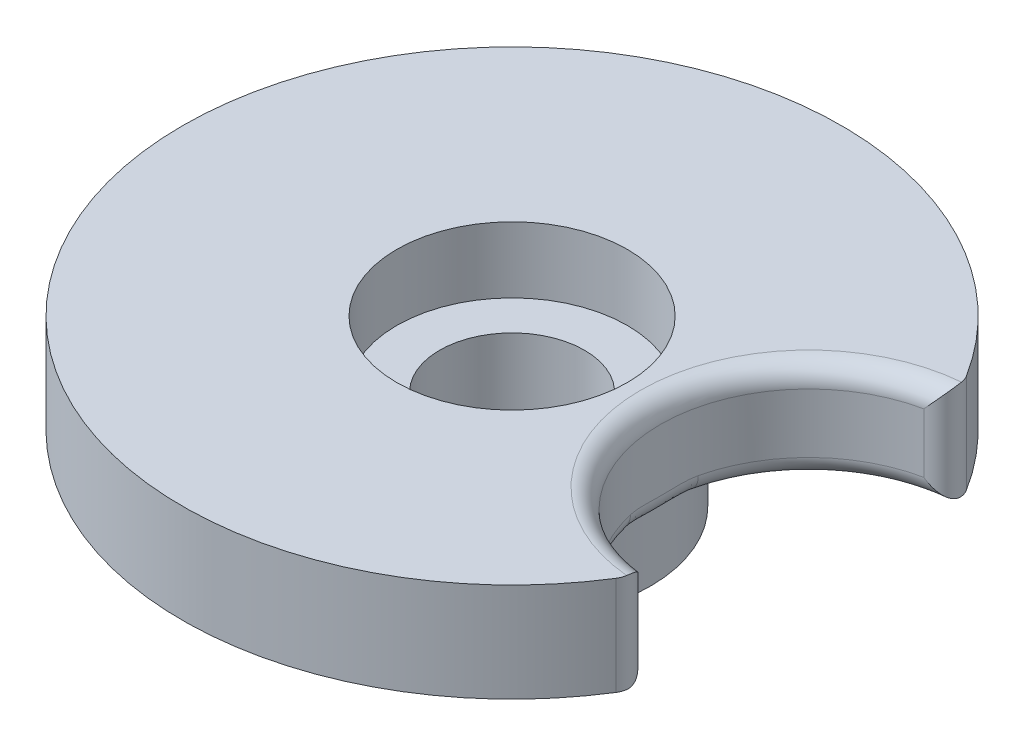
SolidWorks part; units mm, degrees
ref_plane "Front Plane" through (0, 0, 0) normal (0, 0, 1) x (1, 0, 0)
ref_plane "Top Plane" through (0, 0, 0) normal (0, 1, 0) x (1, 0, 0)
ref_plane "Right Plane" through (0, 0, 0) normal (1, 0, 0) x (0, 0, -1)
sketch "Sketch1" plane through (0, 0, 0) normal (0, 1, 0) x (1, 0, 0)
  line L0 (0, 0) -> (11.43, 0) construction
  circle A0 centre (0, 0) radius 12.7 construction
  circle A1 centre (0, 0) radius 2.794
  circle A2 centre (11.43, 0) radius 5.715 construction
  arc A3 (11.3418, 5.7143) -> (11.3418, -5.7143) centre (11.43, 0) ccw
  arc A4 (11.3418, 5.7143) -> (11.3418, -5.7143) centre (0, 0) ccw
  dimension "D1" = 25.4
  dimension "D2" = 5.588
  dimension "D3" = 11.43
  dimension "D4" = 11.43
extrude "Boss-Extrude1" add sketch "Sketch1" along normal blind 3.81 contours A3 A4 A1
sketch "Sketch3" plane through (0, 3.81, 0) normal (0, 1, 0) x (1, 0, 0)
  circle A0 centre (0, 0) radius 4.445
  dimension "D1" = 8.89
extrude "Cut-Extrude1" cut sketch "Sketch3" against normal blind 2.54 contours A0
sketch "Sketch4" plane through (0, 0, 0) normal (0, -1, 0) x (1, 0, 0)
  circle A0 centre (0, 0) radius 2.794
  circle A1 centre (0, 0) radius 5.334
  circle A2 centre (0, 0) radius 2.794 construction
  dimension "D1" = 2.54
extrude "Boss-Extrude2" add sketch "Sketch4" along normal blind 2.54
fillet "Fillet2" radius 0.762 4 edges at (5.715, 0, 0) (5.715, 3.81, 0) (11.3418, 1.905, -5.7143) (11.3418, 1.905, 5.7143)
